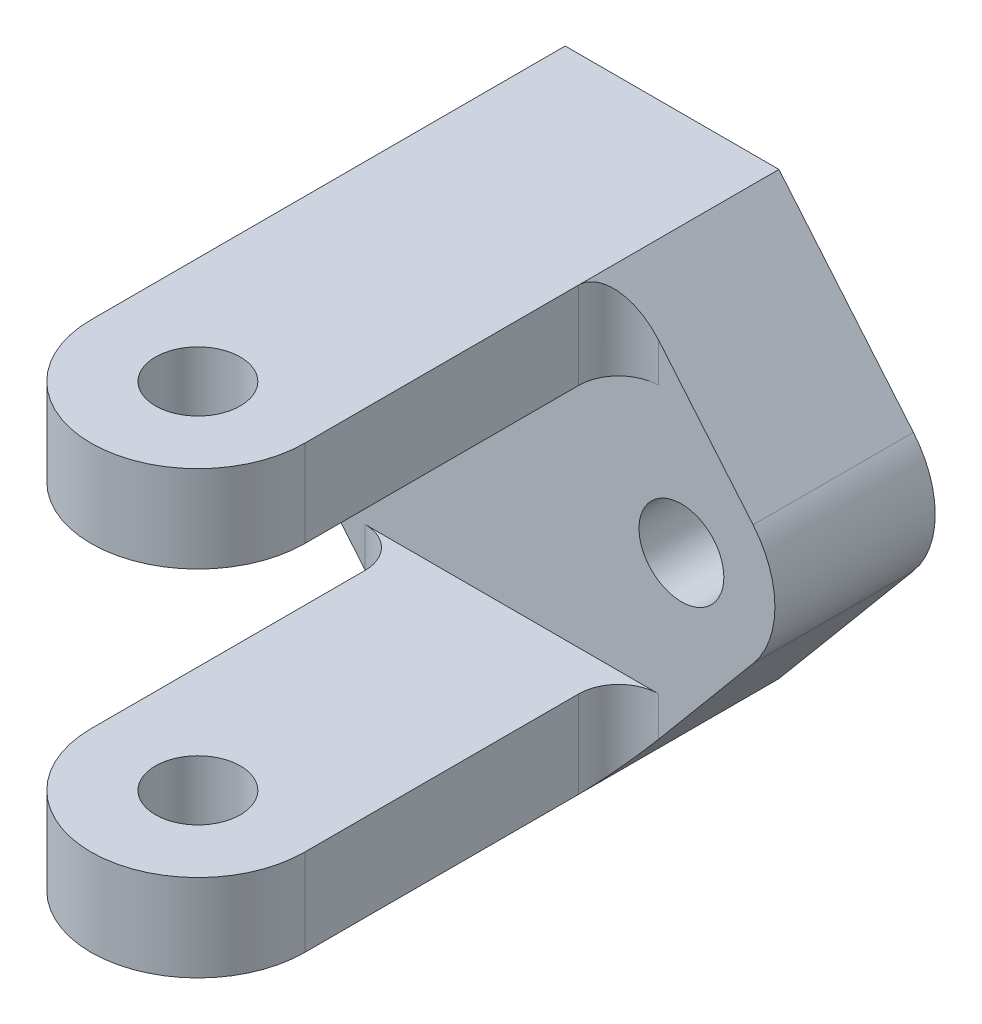
SolidWorks part; units mm, degrees
material "7075-T6 (SN)"
ref_plane "Front Plane" through (0, 0, 0) normal (0, 0, 1) x (1, 0, 0)
ref_plane "Top Plane" through (0, 0, 0) normal (0, 1, 0) x (1, 0, 0)
ref_plane "Right Plane" through (0, 0, 0) normal (1, 0, 0) x (0, 0, -1)
sketch "Sketch1" plane through (0, 0, 0) normal (0, 0, 1) x (1, 0, 0)
  line L0 (12.7, 0) -> (-12.7, 0) construction
  line L1 (-20.7, -16.51) -> (20.7, -16.51)
  line L2 (-20.7, -16.51) -> (-20.7, 16.51)
  line L3 (-20.7, 16.51) -> (20.7, 16.51)
  line L4 (20.7, -16.51) -> (20.7, 16.51)
  line L5 (-20.7, -16.51) -> (20.7, 16.51) construction
  line L6 (-20.7, 16.51) -> (20.7, -16.51) construction
  circle A0 centre (12.7, 0) radius 3.175
  circle A1 centre (-12.7, 0) radius 3.175
  point P0 (0, 0)
  dimension "D1" = 6.35
  dimension "D2" = 25.4
  dimension "D3" = 8
  dimension "D4" = 16.51
extrude "Boss-Extrude1" add sketch "Sketch1" along normal blind 12 contours L3 L4 L1 L2
sketch "Sketch2" plane through (0, 0, 12) normal (0, 0, 1) x (1, 0, 0)
  line L0 (-12.7, 0) -> (12.7, 0) construction
  line L2 (-20.7, 10) -> (20.7, 10)
  line L3 (-20.7, 10) -> (-20.7, 16.51)
  line L4 (-20.7, 16.51) -> (20.7, 16.51)
  line L5 (20.7, 10) -> (20.7, 16.51)
  line L6 (-20.7, 10) -> (20.7, 16.51) construction
  line L7 (-20.7, 16.51) -> (20.7, 10) construction
  line L8 (-20.7, 16.51) -> (-20.7, -16.51) construction
  line L9 (20.7, -10) -> (20.7, -16.51)
  line L10 (-20.7, -10) -> (-20.7, -16.51)
  line L11 (-20.7, -16.51) -> (20.7, -10) construction
  line L12 (-20.7, -10) -> (20.7, -16.51) construction
  line L13 (-20.7, -10) -> (20.7, -10)
  line L14 (-20.7, -16.51) -> (20.7, -16.51)
  circle A0 centre (-12.7, 0) radius 3.175 construction
  circle A1 centre (12.7, 0) radius 3.175 construction
  point P6 (0, 13.255)
  point P21 (0, -13.255)
  dimension "D1" = 20
extrude "Boss-Extrude2" add sketch "Sketch2" along normal blind 53
sketch "Sketch3" plane through (0, 0, 0) normal (0, 1, 0) x (1, 0, 0)
  point P0 (0, -35.5)
  dimension "D1" = 35.5
ref_point "UBJ Point"
sketch "Sketch4" plane through (0, 0, 0) normal (0, 1, 0) x (1, 0, 0)
  circle A0 centre (0, -35.5) radius 3.175
  dimension "D1" = 6.35
extrude "Cut-Extrude1" cut sketch "Sketch4" against normal up to surface and the other way up to surface up to face at (0, -16.51, 32.5) other way up to face at (0, 16.51, 32.5)
sketch "Sketch5" plane through (0, 0, 0) normal (0, 1, 0) x (1, 0, 0)
  line L0 (20.7, -12) -> (8.3595, -39.2814)
  line L1 (-8.3595, -39.2814) -> (-20.7, -12)
  line L4 (20.7, 0) -> (-20.7, 0)
  line L5 (-20.7, 0) -> (-20.7, -65)
  line L6 (-20.7, -65) -> (20.7, -65)
  line L7 (20.7, -65) -> (20.7, 0)
  line L9 (-20.7, -12) -> (-20.7, -65)
  line L10 (-20.7, -65) -> (20.7, -65)
  line L11 (20.7, -65) -> (20.7, -12)
  line L12 (20.7, -12) -> (-20.7, -12)
  line L13 (20.7, -65) -> (20.7, -12)
  line L14 (-20.7, -65) -> (20.7, -65)
  line L15 (-20.7, -12) -> (-20.7, -65)
  line L17 (20.7, -65) -> (20.7, -12)
  line L18 (-20.7, -65) -> (20.7, -65)
  line L19 (-20.7, -12) -> (-20.7, -65)
  arc A0 (-8.3595, -39.2814) -> (8.3595, -39.2814) centre (0, -35.5) ccw
  circle A1 centre (0, -35.5) radius 3.175 construction
  circle A2 centre (0, -35.5) radius 3.175 construction
  dimension "D3" = 6
  dimension "D1" = 0
  dimension "D2" = 0
extrude "Cut-Extrude2" [suppressed] cut sketch "Sketch5" against normal up to surface and the other way up to surface contours A0 L1 L9 L10 L11 L0
sketch "Sketch6" plane through (0, 0, 0) normal (0, 1, 0) x (1, 0, 0)
  line L0 (-8, -35.5) -> (-8, -20)
  line L1 (8, -35.5) -> (8, -20)
  line L2 (-16, -12) -> (-20.7, -12)
  line L3 (-8, -20) -> (-8, -12)
  line L4 (20.7, -12) -> (-20.7, -12)
  line L5 (-20.7, -12) -> (-20.7, -65)
  line L6 (-20.7, -65) -> (20.7, -65)
  line L7 (20.7, -65) -> (20.7, -12)
  line L8 (20.7, -12) -> (16, -12)
  line L9 (-20.7, -12) -> (-20.7, -65)
  line L10 (-20.7, -65) -> (20.7, -65)
  line L11 (20.7, -65) -> (20.7, -12)
  line L12 (-8, -12) -> (-16, -12)
  line L13 (8, -20) -> (8, -12)
  line L14 (8, -12) -> (16, -12)
  arc A0 (-8, -35.5) -> (8, -35.5) centre (0, -35.5) ccw
  circle A1 centre (0, -35.5) radius 3.175 construction
  arc A2 (-8, -20) -> (-16, -12) centre (-16, -20) ccw construction
  arc A3 (8, -20) -> (16, -12) centre (16, -20) cw construction
  dimension "D2" = 8
  dimension "D3" = 8
  dimension "D1" = 0
extrude "Cut-Extrude3" cut sketch "Sketch6" against normal up to surface and the other way up to surface up to face at (0, -16.51, 38.675) other way up to face at (0, 16.51, 32.325)
fillet "Fillet1" [suppressed] radius 12.7
sketch "Sketch7" plane through (0, 0, 0) normal (0, 0, 1) x (1, 0, 0)
  line L0 (-12.7, 7) -> (-8, 7)
  line L1 (-12.7, -7) -> (-8, -7)
  line L2 (-8, 16.51) -> (-8, 7)
  line L3 (-8, -16.51) -> (-8, -7)
  line L4 (0, 10.3988) -> (0, -8.4154) construction
  line L5 (8, -16.51) -> (8, -7)
  line L6 (20.7, -16.51) -> (8, -16.51)
  line L7 (20.7, 16.51) -> (20.7, -16.51)
  line L8 (8, 16.51) -> (20.7, 16.51)
  line L9 (8, 16.51) -> (8, 7)
  line L10 (12.7, 7) -> (8, 7)
  line L11 (12.7, -7) -> (8, -7)
  line L12 (8, 10) -> (-8, 10)
  line L13 (-8, 10) -> (-8, 16.51)
  line L14 (-8, 16.51) -> (-20.7, 16.51)
  line L15 (-20.7, 16.51) -> (-20.7, -16.51)
  line L16 (-20.7, -16.51) -> (-8, -16.51)
  line L17 (-8, -16.51) -> (-8, -10)
  line L18 (-8, -10) -> (8, -10)
  line L19 (8, -10) -> (8, -16.51)
  line L20 (8, -16.51) -> (20.7, -16.51)
  line L21 (20.7, -16.51) -> (20.7, 16.51)
  line L22 (20.7, 16.51) -> (8, 16.51)
  line L23 (8, 16.51) -> (8, 10)
  line L26 (-8, 16.51) -> (-20.7, 16.51)
  line L27 (-20.7, 16.51) -> (-20.7, -16.51)
  line L28 (-20.7, -16.51) -> (-8, -16.51)
  line L32 (8, -16.51) -> (20.7, -16.51)
  line L33 (20.7, -16.51) -> (20.7, 16.51)
  line L34 (20.7, 16.51) -> (8, 16.51)
  line L36 (-8, 10) -> (8, 10) construction
  line L37 (8, -10) -> (-8, -10) construction
  line L38 (-8, 10) -> (8, 10)
  line L39 (8, -10) -> (-8, -10)
  arc A0 (-12.7, 7) -> (-12.7, -7) centre (-12.7, 0) ccw
  circle A1 centre (-12.7, 0) radius 3.175 construction
  arc A2 (12.7, 7) -> (12.7, -7) centre (12.7, 0) cw
  dimension "D2" = 7
  dimension "D1" = 0
extrude "Cut-Extrude4" cut sketch "Sketch7" along normal up to surface (12 mm away) contours A0 L0 L2 L26 L27 L28 L3 L1 | L10 A2 L11 L5 L6 L7 L8 L9 up to face at (0, 0, 12)
fillet "Fillet2" [suppressed] radius 5
sketch "Sketch8" plane through (0, 0, 0) normal (0, 0, 1) x (1, 0, 0)
  line L0 (12.7, 7) -> (8, 7) construction
  line L1 (8, 16.51) -> (8, 7) construction
  line L2 (12.7, 7) -> (8, 7)
  line L3 (8, 16.51) -> (8, 7)
  line L4 (6.7586, 0) -> (-5.803, 0) construction
  line L5 (0, 7.1591) -> (0, -7.1591) construction
  line L6 (8, 16.51) -> (18.0658, 4.4954)
  line L7 (-8, 16.51) -> (-8, 7)
  line L8 (-12.7, 7) -> (-8, 7)
  line L9 (-8, 16.51) -> (-18.0658, 4.4954)
  line L10 (-8, -16.51) -> (-18.0658, -4.4954)
  line L11 (-12.7, -7) -> (-8, -7)
  line L12 (-8, -16.51) -> (-8, -7)
  line L13 (8, -16.51) -> (8, -7)
  line L14 (12.7, -7) -> (8, -7)
  line L15 (8, -16.51) -> (18.0658, -4.4954)
  arc A0 (12.7, -7) -> (12.7, 7) centre (12.7, 0) ccw construction
  arc A1 (18.0658, 4.4954) -> (12.7, 7) centre (12.7, 0) ccw
  arc A2 (-18.0658, 4.4954) -> (-12.7, 7) centre (-12.7, 0) cw
  arc A3 (-18.0658, -4.4954) -> (-12.7, -7) centre (-12.7, 0) ccw
  arc A4 (18.0658, -4.4954) -> (12.7, -7) centre (12.7, 0) cw
extrude "Boss-Extrude3" add sketch "Sketch8" along normal up to surface (12 mm away) contours L15 A4 L14 L13 | A3 L10 L12 L11 | L6 A1 L2 L3 | L9 A2 L8 L7 up to face at (-9.525, 0, 12)
fillet "Fillet3" radius 3 3 edges at (8, 13.255, 12) (-8, 13.255, 12) (8, -13.255, 12)
